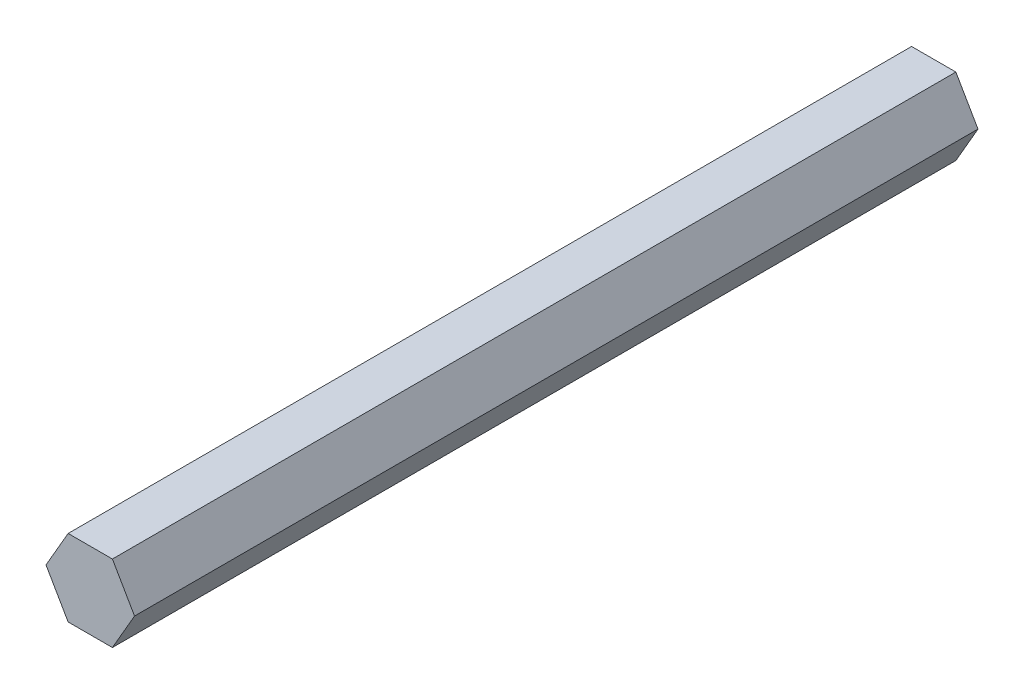
SolidWorks part; units mm, degrees
ref_plane "Front Plane" through (0, 0, 0) normal (0, 0, 1) x (1, 0, 0)
ref_plane "Top Plane" through (0, 0, 0) normal (0, 1, 0) x (1, 0, 0)
ref_plane "Right Plane" through (0, 0, 0) normal (1, 0, 0) x (0, 0, -1)
sketch "Sketch1" plane through (0, 0, 0) normal (0, 0, 1) x (1, 0, 0)
  line L1 (1.4434, -2.5) -> (2.8868, 0)
  line L2 (2.8868, 0) -> (1.4434, 2.5)
  line L3 (1.4434, 2.5) -> (-1.4434, 2.5)
  line L4 (-1.4434, 2.5) -> (-2.8868, 0)
  line L5 (-2.8868, 0) -> (-1.4434, -2.5)
  line L6 (-1.4434, -2.5) -> (1.4434, -2.5)
  circle A0 centre (0, 0) radius 2.5 construction
  dimension "D1" = 5
extrude "Boss-Extrude1" add sketch "Sketch1" along normal blind 55
